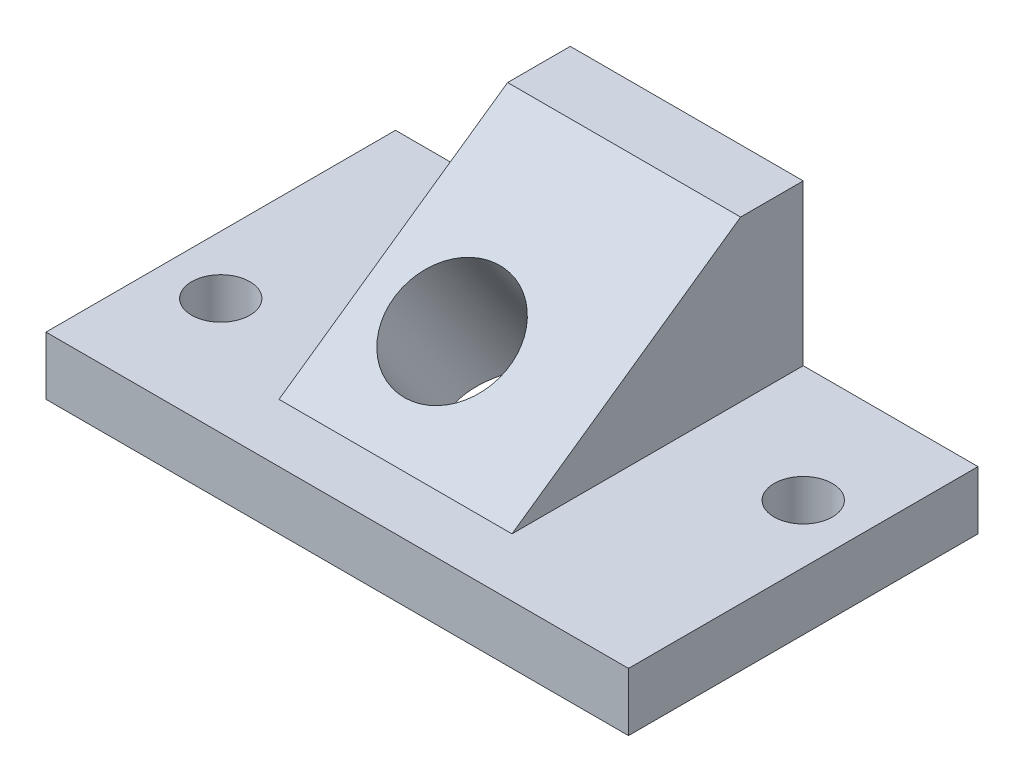
SolidWorks part; units mm, degrees
other "DetailItem5"
other "DetailItem6"
other "DetailItem7"
ref_plane "Front" through (0, 0, 0) normal (0, 0, 1) x (1, 0, 0)
ref_plane "Top" through (0, 0, 0) normal (0, 1, 0) x (1, 0, 0)
ref_plane "Right" through (0, 0, 0) normal (1, 0, 0) x (0, 0, -1)
sketch "Sketch1" plane through (0, 0, 0) normal (0, 1, 0) x (1, 0, 0)
  line L0 (-63.5, -38.1) -> (63.5, -38.1)
  line L1 (-63.5, -38.1) -> (-63.5, 38.1)
  line L2 (63.5, 38.1) -> (-63.5, 38.1)
  line L3 (63.5, 38.1) -> (63.5, -38.1)
  line L4 (-63.5, 38.1) -> (63.5, -38.1) construction
  dimension "D1" = 127
  dimension "D2" = 76.2
extrude "Base-Extrude" add sketch "Sketch1" along normal blind 12.7
sketch "Sketch3" plane through (0, 0, 0) normal (1, 0, 0) x (0, 0, -1)
  line L0 (-25.4, 12.7) -> (24.4424, 47.6)
  line L1 (24.4424, 47.6) -> (38.1, 47.6)
  line L2 (38.1, 47.6) -> (38.1, 12.7)
  line L3 (38.1, 12.7) -> (-25.4, 12.7)
  line L4 (-38.1, 12.7) -> (-38.1, 0) construction
  line L5 (38.1, 12.7) -> (-38.1, 12.7) construction
  dimension "D1" = 34.9
  dimension "D2" = 35
  dimension "D3" = 12.7
extrude "Boss-Extrude2" add sketch "Sketch3" against normal mid plane 50.8
sketch "Sketch4" plane through (65.6996, 12.7, 10.1892) normal (0, 1, 0) x (-1, 0, 0)
  line L0 (129.1996, 27.9108) -> (2.1996, 27.9108) construction
  line L1 (2.1996, -48.2892) -> (2.1996, 27.9108) construction
  line L2 (129.1996, 27.9108) -> (129.1996, -48.2892) construction
  line L3 (129.1996, 27.9108) -> (2.1996, 27.9108) construction
  circle A0 centre (14.8996, -22.8892) radius 6.35
  circle A1 centre (116.4996, 2.5108) radius 6.35
  dimension "D1" = 12.7
  dimension "D2" = 12.7
  dimension "D3" = 25.4
  dimension "D4" = 12.7
  dimension "D5" = 50.8
extrude "Cut-Extrude1" cut sketch "Sketch4" against normal through all
sketch "Sketch5" plane through (0, 20.4559, 14.3234) normal (0, 0.8192, 0.5736) x (-1, 0, 0)
  line L0 (25.4, 13.522) -> (25.4, -47.3243) construction
  line L1 (25.4, -47.3243) -> (-25.4, -47.3243) construction
  circle A0 centre (6.3, -9.2243) radius 12.7
  dimension "D3" = 25.4
  dimension "D1" = 19.1
  dimension "D2" = 38.1
extrude "Cut-Extrude2" cut sketch "Sketch5" against normal through all
